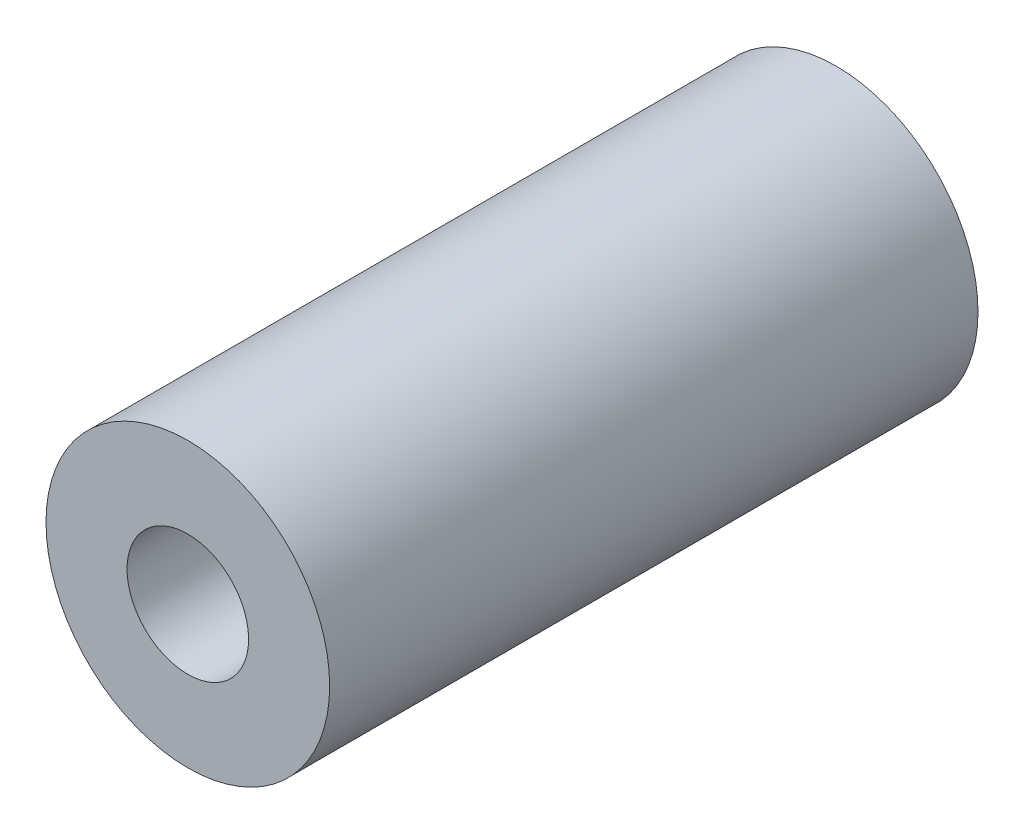
SolidWorks part; units mm, degrees
ref_plane "前视基准面" through (0, 0, 0) normal (0, 0, 1) x (1, 0, 0)
ref_plane "上视基准面" through (0, 0, 0) normal (0, 1, 0) x (1, 0, 0)
ref_plane "右视基准面" through (0, 0, 0) normal (1, 0, 0) x (0, 0, -1)
sketch "草图1" plane through (0, 0, 0) normal (0, 0, 1) x (1, 0, 0)
  circle A0 centre (0, 0) radius 3.5
  circle A1 centre (0, 0) radius 1.5
  dimension "D1" = 7
  dimension "D2" = 3
extrude "拉伸1" add sketch "草图1" along normal blind 16
